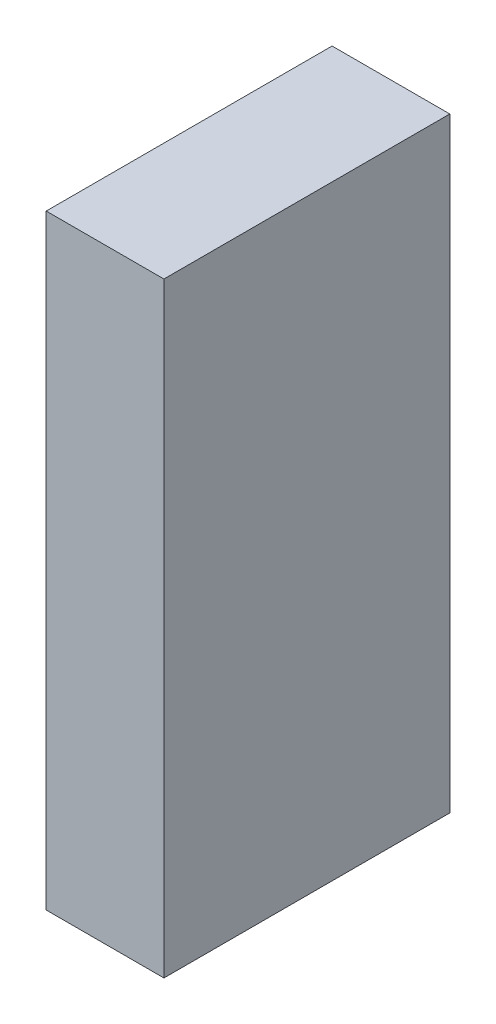
SolidWorks part; units mm, degrees
ref_plane "Alzado" through (0, 0, 0) normal (0, 0, 1) x (1, 0, 0)
ref_plane "Planta" through (0, 0, 0) normal (0, 1, 0) x (1, 0, 0)
ref_plane "Vista lateral" through (0, 0, 0) normal (1, 0, 0) x (0, 0, -1)
sketch "Croquis1" plane through (0, 0, 0) normal (0, 1, 0) x (1, 0, 0)
  line L1 (-6.0669, -9.0372) -> (7.9331, -9.0372)
  line L2 (-6.0669, -9.0372) -> (-6.0669, 24.9628)
  line L3 (-6.0669, 24.9628) -> (7.9331, 24.9628)
  line L4 (7.9331, -9.0372) -> (7.9331, 24.9628)
  dimension "D1" = 34
  dimension "D2" = 14
extrude "Saliente-Extruir1" add sketch "Croquis1" along normal blind 72
